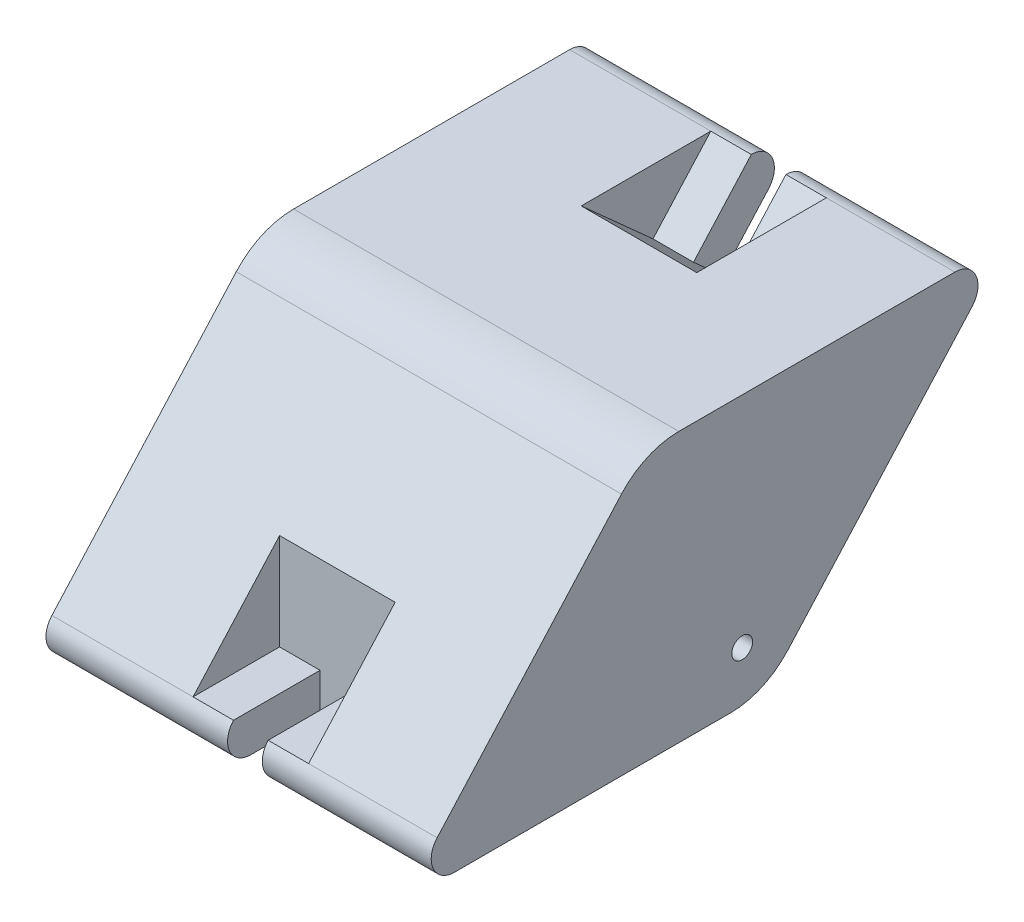
SolidWorks part; units mm, degrees
ref_plane "Front Plane" through (0, 0, 0) normal (0, 0, 1) x (1, 0, 0)
ref_plane "Top Plane" through (0, 0, 0) normal (0, 1, 0) x (1, 0, 0)
ref_plane "Right Plane" through (0, 0, 0) normal (1, 0, 0) x (0, 0, -1)
sketch "Sketch4" plane through (0, 0, 0) normal (1, 0, 0) x (0, 0, -1)
  line L4 (-14.0132, 16.5502) -> (21.8223, 16.5502)
  line L5 (-21.4568, 13.228) -> (-45.3869, -13.4464)
  line L6 (24.0553, 11.5469) -> (0.1252, -15.1276)
  line L7 (-43.1539, -18.4498) -> (-7.3184, -18.4498)
  line L8 (28.5439, 16.5502) -> (-49.8755, -18.4498) construction
  line L9 (-18.4764, 16.5502) -> (-2.8552, -18.4498) construction
  circle A0 centre (-5.9527, -11.5096) radius 3.6
  arc A1 (-7.3184, -18.4498) -> (0.1252, -15.1276) centre (-7.3184, -8.4498) ccw
  arc A2 (-45.3869, -13.4464) -> (-43.1539, -18.4498) centre (-43.1539, -15.4498) ccw
  arc A3 (24.0553, 11.5469) -> (21.8223, 16.5502) centre (21.8223, 13.5502) ccw
  arc A4 (-21.4568, 13.228) -> (-14.0132, 16.5502) centre (-14.0132, 6.5502) cw
  dimension "D3" = 7.2
  dimension "D5" = 10
  dimension "D6" = 3
  dimension "D7" = 3
  dimension "D8" = 10
  dimension "D1" = 35
  dimension "D2" = 35
  dimension "D4" = 7.6
extrude "ThickBase" add sketch "Sketch4" along normal blind 10
sketch "Sketch5" plane through (10, 0, 0) normal (1, 0, 0) x (0, 0, -1)
  line L0 (-43.1539, -18.4498) -> (-7.3184, -18.4498) construction
  line L1 (0.1252, -15.1276) -> (24.0553, 11.5469) construction
  line L2 (15.9453, 2.5068) -> (24.0553, 11.5469)
  line L3 (21.8223, 16.5502) -> (-14.0132, 16.5502)
  line L4 (21.8223, 16.5502) -> (-14.0132, 16.5502) construction
  line L5 (-21.4568, 13.228) -> (-45.3869, -13.4464)
  line L6 (-43.1539, -18.4498) -> (-31.0091, -18.4498)
  circle A0 centre (-5.9527, -11.5096) radius 24 construction
  arc A1 (-31.0091, -18.4498) -> (15.9453, 2.5068) centre (-5.9527, -11.5096) cw
  arc A2 (-43.1539, -18.4498) -> (-45.3869, -13.4464) centre (-43.1539, -15.4498) cw
  arc A3 (-45.3869, -13.4464) -> (-43.1539, -18.4498) centre (-43.1539, -15.4498) ccw construction
  arc A4 (24.0553, 11.5469) -> (21.8223, 16.5502) centre (21.8223, 13.5502) ccw
  arc A5 (24.0553, 11.5469) -> (21.8223, 16.5502) centre (21.8223, 13.5502) ccw construction
  arc A6 (-14.0132, 16.5502) -> (-21.4568, 13.228) centre (-14.0132, 6.5502) ccw
  arc A7 (-14.0132, 16.5502) -> (-21.4568, 13.228) centre (-14.0132, 6.5502) ccw construction
  dimension "D1" = 25.9997
extrude "Middle" add sketch "Sketch5" along normal blind 35
sketch "Sketch7" plane through (45, 0, 0) normal (1, 0, 0) x (0, 0, -1)
  line L0 (-45.3869, -13.4464) -> (-21.4568, 13.228)
  line L1 (-14.0132, 16.5502) -> (21.8223, 16.5502)
  line L7 (0.1252, -15.1276) -> (24.0553, 11.5469)
  line L8 (-7.3184, -18.4498) -> (-43.1539, -18.4498)
  arc A0 (-43.1539, -18.4498) -> (-45.3869, -13.4464) centre (-43.1539, -15.4498) cw
  arc A1 (-45.3869, -13.4464) -> (-43.1539, -18.4498) centre (-43.1539, -15.4498) ccw construction
  arc A2 (-21.4568, 13.228) -> (-14.0132, 16.5502) centre (-14.0132, 6.5502) cw
  arc A3 (-14.0132, 16.5502) -> (-21.4568, 13.228) centre (-14.0132, 6.5502) ccw construction
  arc A4 (21.8223, 16.5502) -> (24.0553, 11.5469) centre (21.8223, 13.5502) cw
  arc A5 (24.0553, 11.5469) -> (21.8223, 16.5502) centre (21.8223, 13.5502) ccw construction
  arc A9 (0.1252, -15.1276) -> (-7.3184, -18.4498) centre (-7.3184, -8.4498) cw
  arc M3 (-31.0091, -18.4498) -> (15.9453, 2.5068) centre (-5.9527, -11.5096) cw
  line M4 (15.9453, 2.5068) -> (24.0553, 11.5469)
  arc M5 (24.0553, 11.5469) -> (21.8223, 16.5502) centre (21.8223, 13.5502) ccw
  line M6 (21.8223, 16.5502) -> (-14.0132, 16.5502)
  arc M7 (-14.0132, 16.5502) -> (-21.4568, 13.228) centre (-14.0132, 6.5502) ccw
  line M8 (-21.4568, 13.228) -> (-45.3869, -13.4464)
  arc M9 (-45.3869, -13.4464) -> (-43.1539, -18.4498) centre (-43.1539, -15.4498) ccw
  line M10 (-43.1539, -18.4498) -> (-31.0091, -18.4498)
extrude "ThinBase" add sketch "Sketch7" along normal blind 5 contours A9 L7 L8 M3 | M10 M3 M4 M5 M6 M7 M8 M9
sketch "Sketch8" plane through (50, 0, 0) normal (1, 0, 0) x (0, 0, -1)
  line L0 (24.0553, 11.5469) -> (-7.2859, -23.3885) construction
  line L1 (-43.1539, -18.4498) -> (5.9786, -18.4498) construction
  line L2 (21.8223, 16.5502) -> (-40.1855, 16.5502) construction
  line L3 (-45.3869, -13.4464) -> (-21.4568, 13.228) construction
  line L4 (-21.4568, 13.228) -> (-14.3706, 21.1268) construction
  line L5 (-18.4764, 16.5502) -> (-2.8552, -18.4498) construction
  circle A0 centre (-5.7897, -11.8749) radius 1.35
  point P0 (-5.7897, -11.8749)
  point P8 (-2.8552, -18.4498)
  point P16 (-18.4764, 16.5502)
  dimension "D3" = 2.7
  dimension "D1" = 7.2
  dimension "D2" = 38.3278
extrude "RetainerScrew" cut sketch "Sketch8" against normal up to surface (5 mm away) up to face at (45, -7.5273, 7.7302)
sketch "Sketch9" plane through (45, 0, 0) normal (-1, 0, 0) x (0, 0, 1)
  circle A0 centre (5.7897, -11.8749) radius 1.35
  circle A1 centre (5.7897, -11.8749) radius 3
  dimension "D1" = 6
  dimension "D2" = 2.7
extrude "Spacer" add sketch "Sketch9" along normal blind 7.2
sketch "Sketch10" plane through (0, 16.5642, 18.4638) normal (0, 0.6678, 0.7444) x (1, 0, 0)
  line L0 (25, 27.6587) -> (25, -43.3174) construction
  line L1 (50, 27.6587) -> (0, 27.6587) construction
  line L2 (0, -43.3174) -> (50, -43.3174) construction
  line L3 (25.82, -43.3174) -> (25.82, 27.6587) construction
  line L4 (50, 27.6587) -> (0, 27.6587) construction
  line L5 (28.07, 27.6587) -> (23.57, 27.6587)
  line L6 (28.07, 27.6587) -> (28.07, 15.6587)
  line L7 (28.07, 15.6587) -> (23.57, 15.6587)
  line L8 (23.57, 27.6587) -> (23.57, 15.6587)
  line L9 (50, 24.6587) -> (50, 27.6587) construction
  line L10 (0, 27.6587) -> (0, 24.6587) construction
  dimension "D1" = 0.82
  dimension "D2" = 4.5
  dimension "D3" = 2.25
  dimension "D4" = 12
  dimension "D5" = 0
extrude "ShockHole" cut sketch "Sketch10" against normal up to surface (35 mm away)
sketch "Sketch12" plane through (0, 11.6557, -10.4565) normal (0, 0.7444, -0.6678) x (1, 0, 0)
  line L0 (50, 5.1917) -> (28.07, 5.1917) construction
  line L1 (18.32, -7.3296) -> (33.32, -7.3296)
  line L2 (18.32, -7.3296) -> (18.32, 5.1917)
  line L3 (18.32, 5.1917) -> (33.32, 5.1917)
  line L4 (33.32, -7.3296) -> (33.32, 5.1917)
  line L5 (25.82, 10.1951) -> (25.82, -7.3296) construction
  line L6 (28.07, 10.1951) -> (23.57, 10.1951) construction
  dimension "D1" = 15
  dimension "D2" = 12.5213
  dimension "D3" = 7.5
extrude "ShockHoleBase" cut sketch "Sketch12" along normal through all
sketch "Sketch11" plane through (0, 16.5502, 0) normal (0, 1, 0) x (1, 0, 0)
  line L0 (28.07, -34.1539) -> (23.57, -34.1539)
  line L1 (28.07, -34.1539) -> (28.07, -46.1539)
  line L2 (28.07, -46.1539) -> (23.57, -46.1539)
  line L3 (23.57, -34.1539) -> (23.57, -46.1539)
  line L4 (25, -46.1539) -> (25, -14.0132) construction
  line L5 (0, -46.1539) -> (50, -46.1539) construction
  line L6 (50, -14.0132) -> (0, -14.0132) construction
  line L7 (25.82, -46.1539) -> (25.82, -14.0132) construction
  dimension "D1" = 4.5
  dimension "D2" = 12
  dimension "D3" = 0.82
  dimension "D4" = 32.1407
  dimension "D5" = 0
  dimension "D6" = 2.25
extrude "ShockHole2" cut sketch "Sketch11" against normal up to surface (35 mm away) up to face at (26.25, -18.4498, 22.1999)
sketch "Sketch13" plane through (0, 0, 34.1539) normal (0, 0, 1) x (1, 0, 0)
  line L0 (50, -13.4464) -> (28.07, -13.4464) construction
  line L1 (18.32, -0.9252) -> (33.32, -0.9252)
  line L2 (18.32, -0.9252) -> (18.32, -13.4464)
  line L3 (18.32, -13.4464) -> (33.32, -13.4464)
  line L4 (33.32, -0.9252) -> (33.32, -13.4464)
  line L5 (25.82, -18.4498) -> (25.82, -0.9252) construction
  line L6 (23.57, -18.4498) -> (28.07, -18.4498) construction
  dimension "D1" = 12.5213
  dimension "D2" = 15
  dimension "D3" = 7.5
extrude "ShockHole2Base" cut sketch "Sketch13" along normal through all
